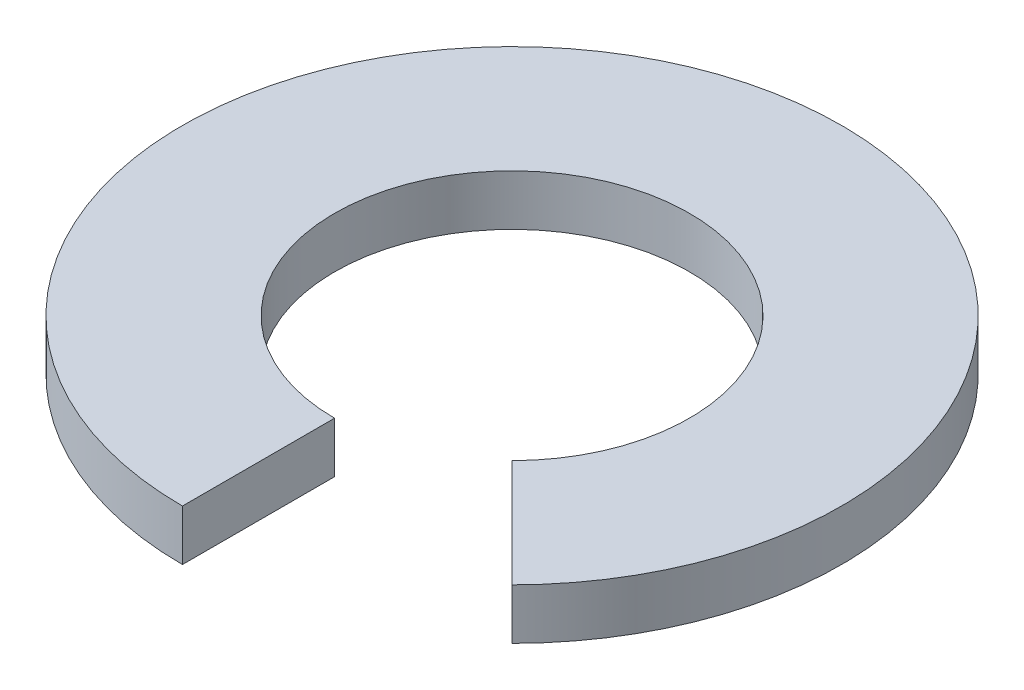
SolidWorks part; units mm, degrees
material "PP homopolímero"
ref_plane "Alzado" through (0, 0, 0) normal (0, 0, 1) x (1, 0, 0)
ref_plane "Planta" through (0, 0, 0) normal (0, 1, 0) x (1, 0, 0)
ref_plane "Vista lateral" through (0, 0, 0) normal (1, 0, 0) x (0, 0, -1)
sketch "Croquis1" plane through (0, 0, 0) normal (0, 1, 0) x (1, 0, 0)
  line L0 (0, -3.5) -> (0, -6.5)
  line L1 (2.4749, -2.4749) -> (4.5962, -4.5962)
  arc A0 (4.5962, -4.5962) -> (0, -6.5) centre (0, 0) ccw
  arc A1 (2.4749, -2.4749) -> (0, -3.5) centre (0, 0) ccw
  dimension "D1" = 7
  dimension "D2" = 13
  dimension "D3" = 45
extrude "Saliente-Extruir1" add sketch "Croquis1" along normal blind 1
